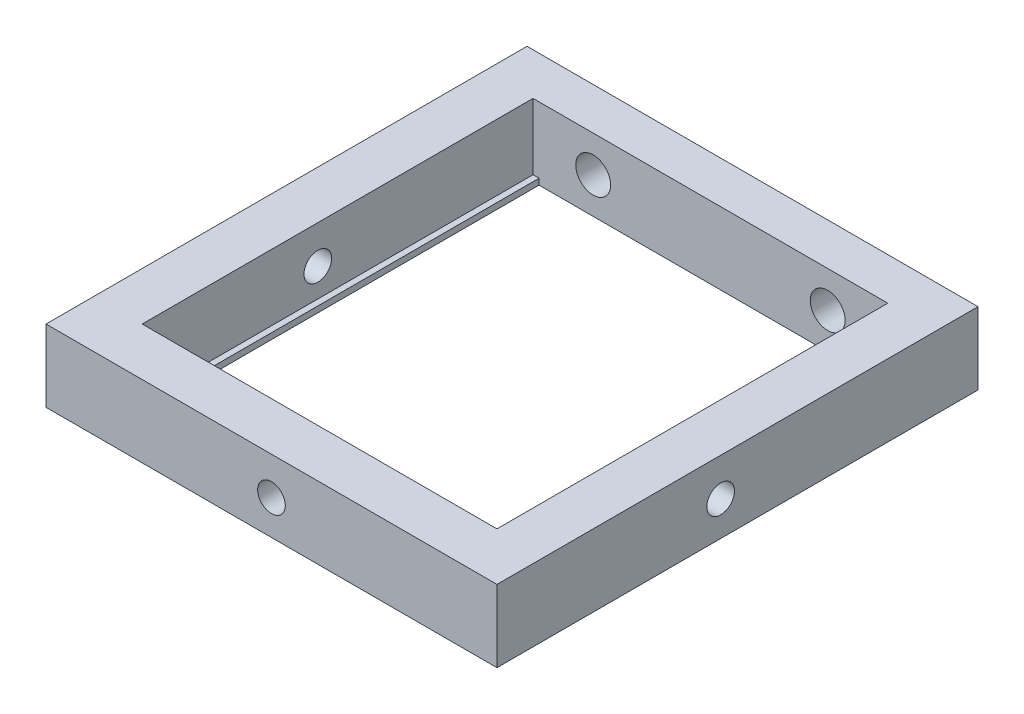
SolidWorks part; units mm, degrees
ref_plane "Front Plane" through (0, 0, 0) normal (0, 0, 1) x (1, 0, 0)
ref_plane "Top Plane" through (0, 0, 0) normal (0, 1, 0) x (1, 0, 0)
ref_plane "Right Plane" through (0, 0, 0) normal (1, 0, 0) x (0, 0, -1)
sketch "Sketch1" plane through (0, 0, 0) normal (0, 1, 0) x (1, 0, 0)
  line L1 (-37.5, -40) -> (37.5, -40)
  line L2 (-37.5, -40) -> (-37.5, 40)
  line L3 (-37.5, 40) -> (37.5, 40)
  line L4 (37.5, -40) -> (37.5, 40)
  line L5 (-37.5, -40) -> (37.5, 40) construction
  line L6 (-37.5, 40) -> (37.5, -40) construction
  point P0 (0, 0)
  dimension "D1" = 80
  dimension "D2" = 75
extrude "Boss-Extrude1" add sketch "Sketch1" along normal blind 12
sketch "Sketch2" plane through (0, 12, 0) normal (0, 1, 0) x (1, 0, 0)
  line L0 (-37.5, 40) -> (-37.5, -40) construction
  line L1 (-29.5, -32) -> (29.5, -32)
  line L2 (-29.5, -32) -> (-29.5, 33)
  line L3 (-29.5, 33) -> (29.5, 33)
  line L4 (29.5, -32) -> (29.5, 33)
  line L5 (37.5, -40) -> (37.5, 40) construction
  line L6 (-37.5, -40) -> (37.5, -40) construction
  line L7 (37.5, 40) -> (-37.5, 40) construction
  dimension "D1" = 8
  dimension "D2" = 8
  dimension "D3" = 8
  dimension "D4" = 7
extrude "Cut-Extrude1" cut sketch "Sketch2" against normal blind 11
sketch "Sketch3" plane through (0, 1, 0) normal (0, 1, 0) x (1, 0, 0)
  line L0 (-29.5, -32) -> (29.5, -32) construction
  line L1 (-27.5, -30) -> (27.5, -30)
  line L2 (-27.5, -30) -> (-27.5, 33)
  line L3 (-27.5, 33) -> (27.5, 33)
  line L4 (27.5, -30) -> (27.5, 33)
  line L5 (-29.5, 33) -> (-29.5, -32) construction
  line L6 (29.5, -32) -> (29.5, 33) construction
  line L7 (37.5, 40) -> (-37.5, 40) construction
  dimension "D1" = 2
  dimension "D2" = 2
  dimension "D3" = 2
  dimension "D4" = 7
extrude "Cut-Extrude2" cut sketch "Sketch3" against normal through all
sketch "Sketch5" plane through (0, 0, -40) normal (0, 0, -1) x (-1, 0, 0)
  line L0 (-37.5, 12) -> (-37.5, 0) construction
  line L1 (37.5, 12) -> (37.5, 0) construction
  circle A0 centre (-19.5, 5.9624) radius 2.9
  circle A1 centre (19.5, 5.9624) radius 2.9
  dimension "D1" = 5.8
  dimension "D2" = 5.8
  dimension "D3" = 18
  dimension "D4" = 18
extrude "Cut-Extrude4" cut sketch "Sketch5" against normal blind 7
sketch "Sketch7" plane through (0, 1, 0) normal (0, 1, 0) x (1, 0, 0)
  line L0 (-27.5, 33) -> (-29.5, 33) construction
  line L1 (-28.5, 33) -> (28.5, 33)
  line L2 (-28.5, 33) -> (-28.5, -31)
  line L3 (-28.5, -31) -> (28.5, -31)
  line L4 (28.5, 33) -> (28.5, -31)
  line L5 (-29.5, 33) -> (-29.5, -32) construction
  line L6 (29.5, -32) -> (29.5, 33) construction
  line L7 (-29.5, -32) -> (29.5, -32) construction
  dimension "D1" = 1
  dimension "D2" = 1
  dimension "D3" = 1
extrude "Cut-Extrude5" cut sketch "Sketch7" against normal through all
sketch "Sketch9" plane through (0, 0, 40) normal (0, 0, 1) x (1, 0, 0)
  line L0 (-37.5, 12) -> (37.5, 12) construction
  line L1 (-37.5, 0) -> (37.5, 0) construction
  line L2 (37.5, 12) -> (37.5, 0) construction
  circle A0 centre (0, 5.75) radius 2.3
  dimension "D1" = 4.6
  dimension "D2" = 6.25
  dimension "D3" = 5.75
  dimension "D4" = 37.5
extrude "Cut-Extrude6" cut sketch "Sketch9" against normal blind 8
sketch "Sketch10" plane through (37.5, 0, 0) normal (1, 0, 0) x (0, 0, -1)
  line L0 (-40, 12) -> (-40, 0) construction
  circle A0 centre (-2.8, 5.7196) radius 2.3
  dimension "D1" = 4.6
  dimension "D2" = 37.2
extrude "Cut-Extrude7" cut sketch "Sketch10" against normal through all
